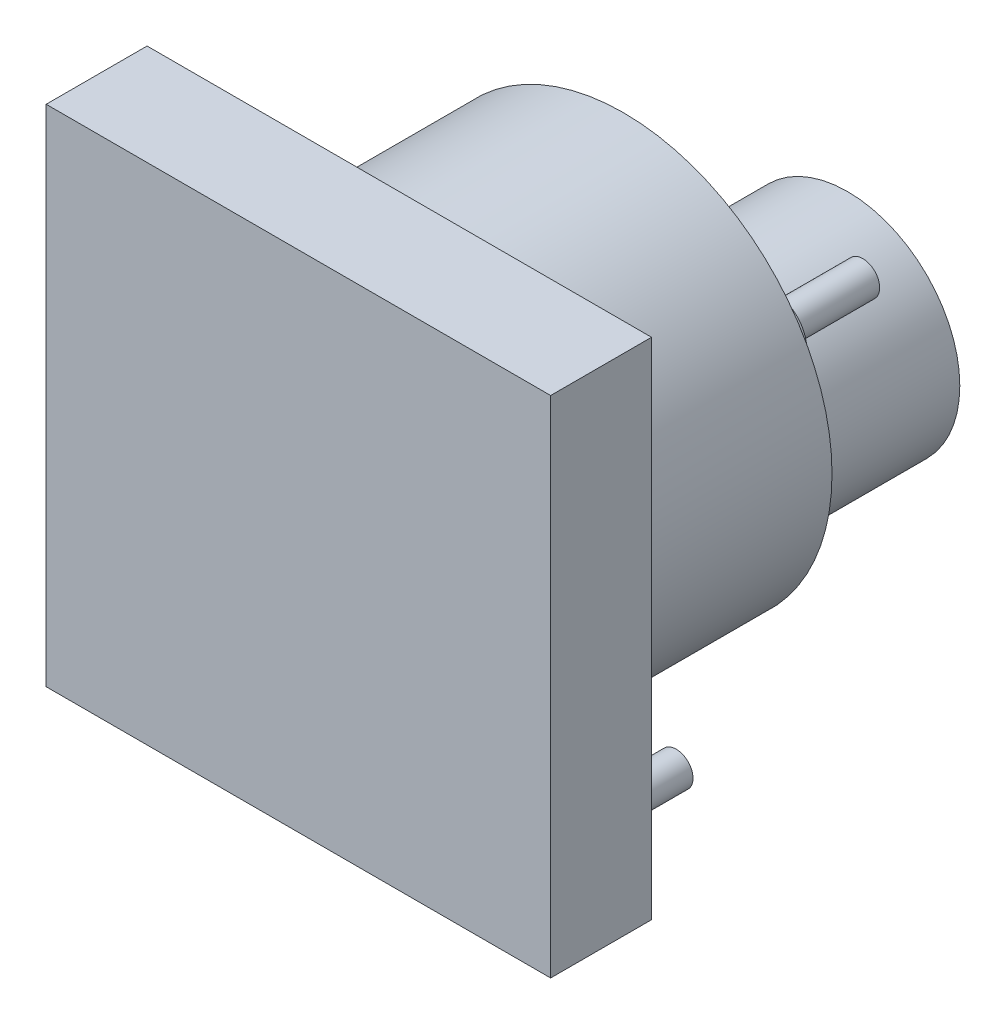
SolidWorks part; units mm, degrees
ref_plane "前视基准面" through (0, 0, 0) normal (0, 0, 1) x (1, 0, 0)
ref_plane "上视基准面" through (0, 0, 0) normal (0, 1, 0) x (1, 0, 0)
ref_plane "右视基准面" through (0, 0, 0) normal (1, 0, 0) x (0, 0, -1)
sketch "草图1" plane through (0, 0, 0) normal (0, 0, 1) x (1, 0, 0)
  line L1 (0, 0) -> (45, 0)
  line L2 (0, 0) -> (0, 45)
  line L3 (0, 45) -> (45, 45)
  line L4 (45, 0) -> (45, 45)
  dimension "D1" = 45
  dimension "D2" = 45
extrude "凸台-拉伸1" add sketch "草图1" against normal blind 9
sketch "草图2" plane through (0, 0, -9) normal (0, 0, -1) x (-1, 0, 0)
  line L0 (0, 45) -> (0, 0) construction
  line L1 (-45, 45) -> (0, 45) construction
  circle A0 centre (-22.5, 22.5) radius 18.6
  dimension "D1" = 22.5
  dimension "D2" = 37.2
  dimension "D3" = 22.5
extrude "凸台-拉伸2" add sketch "草图2" along normal blind 20
sketch "草图3" plane through (0, 0, -29) normal (0, 0, -1) x (-1, 0, 0)
  line L1 (0, 0) -> (-45, 0) construction
  line L2 (-33.85, 29) -> (-11.15, 29) construction
  circle A0 centre (-33.85, 29) radius 3
  circle A1 centre (-11.15, 29) radius 3
  point P4 (-22.5, 29)
  point P5 (-22.5, 0)
  dimension "D1" = 6
  dimension "D2" = 6
  dimension "D3" = 22.7
  dimension "D5" = 29
extrude "凸台-拉伸3" add sketch "草图3" along normal blind 2
sketch "草图4" plane through (0, 0, -31) normal (0, 0, -1) x (-1, 0, 0)
  circle A0 centre (-33.85, 29) radius 1.5
  circle A1 centre (-11.15, 29) radius 1.5
  dimension "D1" = 3
  dimension "D2" = 3
extrude "凸台-拉伸4" add sketch "草图4" along normal blind 8
sketch "草图5" plane through (0, 0, -29) normal (0, 0, -1) x (-1, 0, 0)
  line L0 (0, 0) -> (-45, 0) construction
  circle A0 centre (-22.5, 15) radius 10
  point P2 (0, 0)
  point P5 (-22.5, 0)
  dimension "D1" = 20
  dimension "D2" = 15
extrude "凸台-拉伸5" add sketch "草图5" along normal blind 20
sketch "草图6" plane through (0, 0, -9) normal (0, 0, -1) x (-1, 0, 0)
  line L0 (-39.6, 5.18) -> (-5.4, 5.18) construction
  line L1 (0, 0) -> (-45, 0) construction
  line L2 (0, 45) -> (0, 0) construction
  line L4 (-45, 0) -> (-45, 45) construction
  circle A0 centre (-39.6, 5.18) radius 1.5
  circle A1 centre (-5.4, 5.18) radius 1.5
  dimension "D1" = 3
  dimension "D2" = 3
  dimension "D3" = 5.4
  dimension "D4" = 5.18
  dimension "D5" = 5.4
extrude "凸台-拉伸6" add sketch "草图6" along normal blind 7.6
